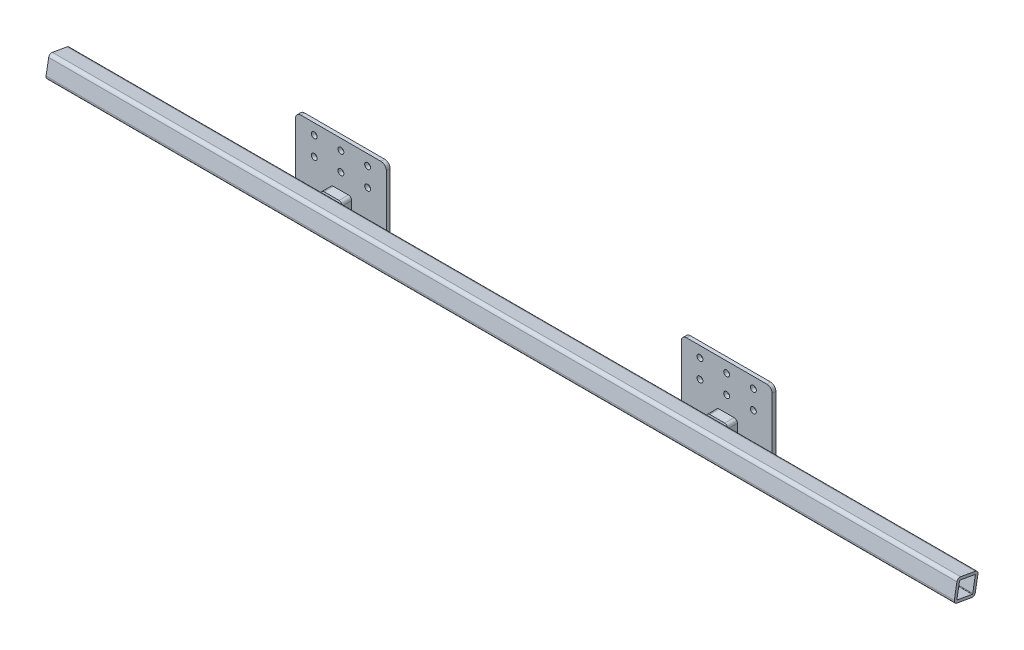
SolidWorks part; units mm, degrees
material "1.0037 (S235JR)"
ref_plane "Płaszczyzna przednia" through (0, 0, 0) normal (0, 0, 1) x (1, 0, 0)
ref_plane "Płaszczyzna górna" through (0, 0, 0) normal (0, 1, 0) x (1, 0, 0)
ref_plane "Płaszczyzna prawa" through (0, 0, 0) normal (1, 0, 0) x (0, 0, -1)
sketch "Szkic1" plane through (0, 0, 0) normal (0, 0, 1) x (1, 0, 0)
  line L0 (0, 70.851) -> (0, -151.9204) construction
  line L1 (-436, 0) -> (-286, 0)
  line L2 (-446, 10) -> (-446, 120)
  line L3 (-436, 130) -> (-286, 130)
  line L4 (-276, 10) -> (-276, 120)
  line L5 (276, 10) -> (276, 120)
  line L6 (436, 130) -> (286, 130)
  line L7 (446, 10) -> (446, 120)
  line L8 (436, 0) -> (286, 0)
  circle A0 centre (-411, 110) radius 5.5
  circle A1 centre (-361, 110) radius 5.5
  circle A2 centre (-311, 110) radius 5.5
  arc A3 (-446, 120) -> (-436, 130) centre (-436, 120) cw
  arc A4 (-286, 130) -> (-276, 120) centre (-286, 120) cw
  arc A5 (-286, 0) -> (-276, 10) centre (-286, 10) ccw
  arc A6 (-436, 0) -> (-446, 10) centre (-436, 10) cw
  arc A7 (436, 0) -> (446, 10) centre (436, 10) ccw
  arc A8 (286, 0) -> (276, 10) centre (286, 10) cw
  arc A9 (286, 130) -> (276, 120) centre (286, 120) ccw
  arc A10 (446, 120) -> (436, 130) centre (436, 120) ccw
  circle A11 centre (311, 110) radius 5.5
  circle A12 centre (361, 110) radius 5.5
  circle A13 centre (411, 110) radius 5.5
  circle A14 centre (-411, 75) radius 5.5
  circle A15 centre (-361, 75) radius 5.5
  circle A16 centre (-311, 75) radius 5.5
  circle A17 centre (311, 75) radius 5.5
  circle A18 centre (361, 75) radius 5.5
  circle A19 centre (411, 75) radius 5.5
  point P15 (-361, 130)
  point P18 (-446, 130)
  point P21 (-276, 130)
  point P24 (-276, 0)
  point P27 (-446, 0)
  point P46 (446, 0)
  point P47 (276, 0)
  point P48 (276, 130)
  point P49 (446, 130)
  dimension "D4" = 11
  dimension "D8" = 10
  dimension "D1" = 622
  dimension "D2" = 170
  dimension "D3" = 130
  dimension "D5" = 20
  dimension "D6" = 50
  dimension "D7" = 50
  dimension "D9" = 35
extrude "Dodanie-wyciągnięcie1" add sketch "Szkic1" along normal blind 5 and the other way blind 2
sketch "Szkic2" plane through (0, 0, 0) normal (1, 0, 0) x (0, 0, -1)
  line L0 (-28.5438, 45.4342) -> (-56.1184, 50.2963)
  line L1 (-63.0691, 45.4294) -> (-67.9313, 17.8548)
  line L2 (-63.0643, 10.904) -> (-35.4897, 6.0419)
  line L3 (-28.5389, 10.9088) -> (-23.6768, 38.4835)
  line L4 (-5, 10) -> (-5, 120) construction
  line L5 (-43.9188, 7.5282) -> (-29.5808, 5) construction
  line L6 (-29.412, 40.5102) -> (-56.9866, 45.3723)
  line L7 (-58.1451, 44.5611) -> (-63.0072, 16.9865)
  line L8 (-62.1961, 15.8281) -> (-34.6214, 10.9659)
  line L9 (-33.463, 11.7771) -> (-28.6008, 39.3517)
  line L10 (-27.4319, 17.1869) -> (-29.5808, 5) construction
  arc A0 (-67.9313, 17.8548) -> (-63.0643, 10.904) centre (-62.0224, 16.8129) ccw
  arc A1 (-35.4897, 6.0419) -> (-28.5389, 10.9088) centre (-34.4478, 11.9507) ccw
  arc A2 (-56.1184, 50.2963) -> (-63.0691, 45.4294) centre (-57.1603, 44.3875) ccw
  arc A3 (-28.5438, 45.4342) -> (-23.6768, 38.4835) centre (-29.5856, 39.5254) cw
  arc A4 (-56.9866, 45.3723) -> (-58.1451, 44.5611) centre (-57.1603, 44.3875) ccw
  arc A5 (-63.0072, 16.9865) -> (-62.1961, 15.8281) centre (-62.0224, 16.8129) ccw
  arc A6 (-34.6214, 10.9659) -> (-33.463, 11.7771) centre (-34.4478, 11.9507) ccw
  arc A7 (-29.412, 40.5102) -> (-28.6008, 39.3517) centre (-29.5856, 39.5254) cw
  point P11 (-68.9731, 11.9459)
  point P16 (-62.0272, 51.3382)
  point P19 (-22.6349, 44.3923)
  dimension "D5" = 6
  dimension "D1" = 10
  dimension "D2" = 40
  dimension "D3" = 40
  dimension "D4" = 70
  dimension "D7" = 5
  dimension "D6" = 5
extrude "Dodanie-wyciągnięcie2" add sketch "Szkic2" along normal blind 850 and the other way blind 850 separate body
sketch "Szkic3" plane through (0, 0, 5) normal (0, 0, -1) x (-1, 0, 0)
  line L0 (375, 45) -> (347, 45)
  line L1 (341, 39) -> (341, 11)
  line L2 (347, 5) -> (375, 5)
  line L3 (381, 11) -> (381, 39)
  line L4 (436, 0) -> (286, 0) construction
  line L5 (286, 130) -> (436, 130) construction
  line L6 (375, 41) -> (347, 41)
  line L7 (345, 39) -> (345, 11)
  line L8 (347, 9) -> (375, 9)
  line L9 (377, 11) -> (377, 39)
  line L10 (0, 90.6997) -> (0, -66.5042) construction
  line L11 (-377, 11) -> (-377, 39)
  line L12 (-347, 9) -> (-375, 9)
  line L13 (-345, 39) -> (-345, 11)
  line L14 (-375, 41) -> (-347, 41)
  line L15 (-381, 11) -> (-381, 39)
  line L16 (-347, 5) -> (-375, 5)
  line L17 (-341, 39) -> (-341, 11)
  line L18 (-375, 45) -> (-347, 45)
  arc A0 (341, 11) -> (347, 5) centre (347, 11) ccw
  arc A1 (375, 5) -> (381, 11) centre (375, 11) ccw
  arc A2 (347, 45) -> (341, 39) centre (347, 39) ccw
  arc A3 (375, 45) -> (381, 39) centre (375, 39) cw
  arc A4 (347, 41) -> (345, 39) centre (347, 39) ccw
  arc A5 (345, 11) -> (347, 9) centre (347, 11) ccw
  arc A6 (375, 9) -> (377, 11) centre (375, 11) ccw
  arc A7 (375, 41) -> (377, 39) centre (375, 39) cw
  arc A8 (-375, 41) -> (-377, 39) centre (-375, 39) ccw
  arc A9 (-375, 9) -> (-377, 11) centre (-375, 11) cw
  arc A10 (-345, 11) -> (-347, 9) centre (-347, 11) cw
  arc A11 (-347, 41) -> (-345, 39) centre (-347, 39) cw
  arc A12 (-375, 45) -> (-381, 39) centre (-375, 39) ccw
  arc A13 (-347, 45) -> (-341, 39) centre (-347, 39) cw
  arc A14 (-375, 5) -> (-381, 11) centre (-375, 11) cw
  arc A15 (-341, 11) -> (-347, 5) centre (-347, 11) cw
  point P14 (361, 45)
  point P17 (361, 130)
  dimension "D4" = 6
  dimension "D1" = 40
  dimension "D2" = 5
  dimension "D3" = 40
  dimension "D5" = 4
extrude "Dodanie-wyciągnięcie3" add sketch "Szkic3" against normal up to surface (18.5857 mm away) separate body
hole_wizard "Otwór gwintowany M101" positions "Szkic4" profile "Szkic5" tap size "M10" standard "ISO"
sketch "Szkic4" plane through (0, -0.2094, 0.0369) normal (0, -0.9848, 0.1736) x (-1, 0, 0)
  line L0 (850, -63.9997) -> (850, -35.9997) construction
  line L1 (-850, -63.9997) -> (-850, -35.9997) construction
  point P0 (800, -49.9997)
  point P6 (850, -49.9997)
  point P7 (-800, -49.9997)
  point P12 (0, 0)
  point P13 (-850, -49.9997)
  dimension "D1" = 50
  dimension "D2" = 50
sketch "Szkic5" plane through (-800, 8.473, 49.277) normal (1, 0, 0) x (0, -0.1736, -0.9848)
  line L0 (0, 0) -> (0, 30.0537)
  line L1 (0, 30.0537) -> (4.25, 27.5)
  line L2 (4.25, 27.5) -> (4.25, 0)
  line L5 (4.25, 0) -> (0, 0)
  line L10 (0, 30.0537) -> (-4.25, 27.5) construction
  line L11 (0, -6.35) -> (0, 107.95) construction
  dimension "Średnica wiertła gwintu" = 8.5
  dimension "Głębokość otworu gwintowanego" = 27.5
  dimension "Kąt wiertła" = 118
cosmetic thread "Gwint otworu1" parameters "D1"=5, "D2"=10
cosmetic thread "Gwint otworu2" parameters "D1"=5, "D2"=10
